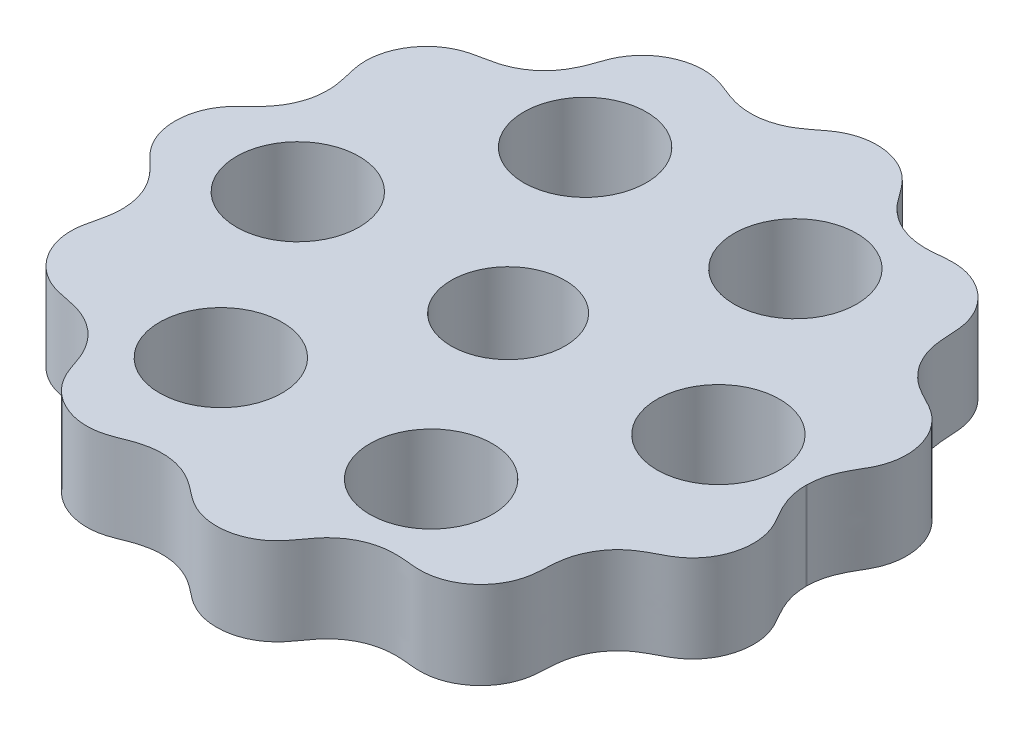
SolidWorks part; units mm, degrees
ref_plane "Front Plane" through (0, 0, 0) normal (0, 0, 1) x (1, 0, 0)
ref_plane "Top Plane" through (0, 0, 0) normal (0, 1, 0) x (1, 0, 0)
ref_plane "Right Plane" through (0, 0, 0) normal (1, 0, 0) x (0, 0, -1)
sketch "Sketch3" plane through (0, 0, 0) normal (0, 1, 0) x (1, 0, 0)
  line L0 (0, 0) -> (12, 0) construction
  circle A2 centre (0, 0) radius 22.0022 construction
  circle A3 centre (0, 0) radius 3.25
  circle A4 centre (12, 0) radius 3.5
  circle A5 centre (6, -10.3923) radius 3.5
  circle A6 centre (-6, -10.3923) radius 3.5
  circle A7 centre (-12, 0) radius 3.5
  circle A8 centre (-6, 10.3923) radius 3.5
  circle A9 centre (6, 10.3923) radius 3.5
  arc A10 (17.0003, 0.0494) -> (17, 0) centre (18.0357, 0.0177) ccw
  spline S0 degree 4 poles (17.0629, 10.5761) (17.1024, 10.5485) (17.1831, 10.4963) (17.3505, 10.4012) (17.7311, 10.208) (18.2739, 9.9208) (18.9393, 9.4712) (19.6343, 8.8352) (20.2276, 8.1035) (20.7083, 7.2937) (21.0679, 6.4232) (21.2996, 5.5105) (21.3985, 4.5738) (21.3612, 3.6327) (21.2084, 2.8227) (20.9929, 2.1509) (20.7619, 1.6146) (20.5771, 1.253) (20.4069, 0.9522) (20.2709, 0.718) (20.1732, 0.544) (20.0996, 0.3974) (20.0548, 0.2883) (20.0293, 0.2059) (20.0151, 0.1485) (20.0054, 0.0954) (19.9994, 0.0221) (19.9995, -0.0231) (20.0056, -0.0976) (20.0157, -0.1515) (20.0305, -0.2103) (20.0576, -0.2961) (20.1054, -0.4102) (20.1837, -0.5637) (20.2872, -0.7462) (20.4299, -0.9919) (20.605, -1.3046) (20.7922, -1.6789) (21.0222, -2.2308) (21.232, -2.918) (21.3741, -3.7456) (21.3939, -4.7048) (21.2722, -5.6618) (21.0101, -6.5953) (20.6114, -7.4854) (20.0808, -8.3094) (19.4318, -9.0448) (18.6765, -9.6692) (17.9593, -10.1033) (17.3838, -10.3747) (17.0159, -10.5949) (16.861, -10.7507) (16.7767, -10.8862) (16.7075, -11.0803) (16.6591, -11.4878) (16.6521, -12.1027) (16.564, -12.9111) (16.3245, -13.8439) (15.9442, -14.7293) (15.4374, -15.5482) (14.8116, -16.287) (14.0807, -16.9293) (13.2585, -17.459) (12.3616, -17.8616) (11.4137, -18.1227) (10.5589, -18.2208) (9.8232, -18.2114) (9.2434, -18.1585) (8.863, -18.1183) (8.5665, -18.1157) (8.3628, -18.1627) (8.2194, -18.2338) (8.0574, -18.3618) (7.797, -18.681) (7.4568, -19.1961) (6.9423, -19.83) (6.2317, -20.4855) (5.4279, -21.024) (4.5537, -21.4367) (3.6266, -21.7155) (2.6684, -21.8557) (1.6984, -21.8537) (0.7392, -21.7074) (-0.1883, -21.4194) (-1.0594, -20.9917) (-1.7352, -20.5281) (-2.2089, -20.1287) (-2.5488, -19.8934) (-2.7398, -19.8138) (-2.897, -19.7836) (-3.1054, -19.7931) (-3.3887, -19.8772) (-3.7411, -20.0221) (-4.2803, -20.2361) (-4.9804, -20.4533) (-5.8246, -20.602) (-6.8039, -20.6219) (-7.7748, -20.4928) (-8.7125, -20.221) (-9.5966, -19.8149) (-10.4092, -19.285) (-11.1316, -18.6426) (-11.751, -17.8996) (-12.248, -17.0704) (-12.563, -16.3174) (-12.7443, -15.7273) (-12.9042, -15.3478) (-13.0235, -15.1793) (-13.1411, -15.0713) (-13.3317, -14.9631) (-13.7448, -14.8538) (-14.3713, -14.7567) (-15.1791, -14.5447) (-16.0776, -14.1626) (-16.9063, -13.6448) (-17.6473, -13.0091) (-18.283, -12.2717) (-18.8012, -11.4523) (-19.1927, -10.5684) (-19.4482, -9.6401) (-19.5636, -8.6834) (-19.5305, -7.721) (-19.3872, -6.9207) (-19.2207, -6.3288) (-19.1523, -5.9241) (-19.1642, -5.7185) (-19.207, -5.5646) (-19.3117, -5.3716) (-19.6027, -5.0567) (-20.0786, -4.6341) (-20.6444, -4.0155) (-21.1932, -3.2033) (-21.6087, -2.3148) (-21.8855, -1.3746) (-22.0173, -0.4082) (-22.0056, 0.5614) (-21.8526, 1.5138) (-21.5633, 2.4285) (-21.1409, 3.29) (-20.6622, 3.9798) (-20.1832, 4.5146) (-19.7733, 4.9083) (-19.5008, 5.1635) (-19.3086, 5.3799) (-19.2098, 5.5586) (-19.1654, 5.7099) (-19.1521, 5.9137) (-19.1968, 6.1997) (-19.2882, 6.5617) (-19.4201, 7.1147) (-19.5338, 7.8237) (-19.5636, 8.663) (-19.453, 9.6163) (-19.2015, 10.5423) (-18.8151, 11.4262) (-18.3005, 12.248) (-17.6671, 12.9896) (-16.9259, 13.6306) (-16.096, 14.1532) (-15.1954, 14.5395) (-14.3851, 14.7539) (-13.7564, 14.8521) (-13.3414, 14.9597) (-13.149, 15.0656) (-13.03, 15.172) (-12.9089, 15.3387) (-12.7477, 15.7162) (-12.5677, 16.3043) (-12.2554, 17.0551) (-11.7627, 17.8827) (-11.1482, 18.6251) (-10.4311, 19.268) (-9.6223, 19.8005) (-8.7401, 20.2108) (-7.8019, 20.4873) (-6.828, 20.6208) (-5.8451, 20.6042) (-4.9974, 20.4574) (-4.2942, 20.2411) (-3.7528, 20.027) (-3.3992, 19.8813) (-3.1154, 19.7953) (-2.9068, 19.7831) (-2.7492, 19.8109) (-2.5577, 19.8882) (-2.2178, 20.1212) (-1.7463, 20.5195) (-1.0739, 20.9828) (-0.2073, 21.4115) (0.7157, 21.7017) (1.6709, 21.8513) (2.639, 21.8576) (3.5979, 21.722) (4.5279, 21.4467) (5.407, 21.036) (6.2156, 20.4983) (6.9308, 19.8426) (7.4486, 19.2074) (7.7905, 18.6908) (8.0504, 18.3693) (8.2113, 18.2391) (8.3536, 18.166) (8.5562, 18.1165) (8.8518, 18.1173) (9.2308, 18.1571) (9.8085, 18.2105) (10.5414, 18.2216) (11.3934, 18.1264) (12.3388, 17.8695) (13.234, 17.472) (14.0571, 16.9469) (14.7909, 16.308) (15.4212, 15.5706) (15.9333, 14.7508) (16.3181, 13.8634) (16.5612, 12.9278) (16.6513, 12.1167) (16.6589, 11.4994) (16.7056, 11.0903) (16.7726, 10.8951) (16.855, 10.7583) (17.0075, 10.6008) (17.3732, 10.3796) (17.9469, 10.1099) (18.6623, 9.6789) (19.4168, 9.059) (20.066, 8.3285) (20.5979, 7.5096) (21, 6.623) (21.2663, 5.6907) (21.3926, 4.7325) (21.3766, 3.7696) (21.2368, 2.9384) (21.0284, 2.248) (20.799, 1.6934) (20.5851, 1.2637) (20.3955, 0.9314) (20.2513, 0.6854) (20.1621, 0.5201) (20.1211, 0.4392) (20.0833, 0.3573) (20.0542, 0.2841) (20.0333, 0.2198) (20.0199, 0.1692) (20.0119, 0.1309) (20.0047, 0.0839) (19.9998, 0.0264) (19.9992, -0.0127) (20.0042, -0.0864) (20.0133, -0.1396) (20.0268, -0.1971) (20.0516, -0.2797) (20.0957, -0.3891) (20.1689, -0.536) (20.2663, -0.71) (20.4023, -0.9443) (20.5727, -1.2448) (20.7579, -1.6062) (20.9896, -2.1421) (21.2061, -2.8134) (21.3601, -3.6231) (21.3988, -4.564) (21.3014, -5.5006) (21.071, -6.4136) (20.7129, -7.2845) (20.2335, -8.095) (19.6414, -8.8276) (18.9476, -9.4646) (18.2831, -9.9152) (17.7408, -10.2031) (17.3601, -10.3961) (17.1925, -10.4908) (17.1115, -10.5425) (17.0719, -10.5698) knots 0 0 0 0 0 0.001143 0.002287 0.004573 0.010154 0.015735 0.021314 0.026894 0.032474 0.038053 0.043633 0.049212 0.054792 0.060372 0.063163 0.065953 0.068667 0.070023 0.07138 0.072395 0.07341 0.073924 0.074181 0.074438 0.074833 0.075229 0.075632 0.076036 0.0763 0.076564 0.077092 0.078165 0.079239 0.080659 0.08208 0.084922 0.087762 0.090603 0.096286 0.101971 0.107653 0.113336 0.119142 0.124948 0.130755 0.13656 0.142365 0.148171 0.15061 0.151699 0.152523 0.153332 0.154393 0.156548 0.162253 0.167957 0.173662 0.179369 0.185074 0.190779 0.196601 0.202423 0.208245 0.214067 0.219889 0.222799 0.22571 0.227909 0.22899 0.229818 0.230629 0.231695 0.233858 0.239585 0.245311 0.251038 0.256767 0.262494 0.268221 0.27397 0.279719 0.285469 0.291218 0.296966 0.302715 0.304886 0.305955 0.30677 0.307594 0.308672 0.310862 0.313762 0.316661 0.322461 0.328262 0.334063 0.339864 0.345664 0.35139 0.357117 0.362845 0.368572 0.374298 0.380024 0.382187 0.383252 0.384064 0.384886 0.385971 0.388401 0.394185 0.399969 0.405752 0.411538 0.417322 0.423106 0.428811 0.434515 0.440221 0.445926 0.451629 0.457334 0.459488 0.460549 0.461358 0.462183 0.463272 0.465711 0.471518 0.477323 0.483129 0.488937 0.494743 0.500549 0.506231 0.511914 0.517598 0.52328 0.528961 0.531802 0.534643 0.53679 0.537846 0.538652 0.539459 0.540515 0.542662 0.545504 0.548346 0.554028 0.559711 0.565396 0.57108 0.576763 0.582568 0.588374 0.59418 0.599985 0.605789 0.611595 0.614033 0.615122 0.615947 0.616756 0.617817 0.619972 0.625677 0.631382 0.637088 0.642795 0.6485 0.654206 0.660027 0.665849 0.67167 0.677492 0.683314 0.686223 0.689133 0.691332 0.692414 0.693241 0.694053 0.695118 0.697281 0.703009 0.708736 0.714464 0.720193 0.725921 0.731648 0.737396 0.743145 0.748894 0.754643 0.76039 0.766138 0.768309 0.769379 0.770193 0.771018 0.772095 0.774286 0.777186 0.780085 0.785886 0.791687 0.797488 0.80329 0.809091 0.814817 0.820543 0.82627 0.831997 0.837722 0.843448 0.84561 0.846676 0.847487 0.848309 0.849394 0.851824 0.857609 0.863393 0.869177 0.874964 0.880748 0.886533 0.892237 0.897941 0.903647 0.909351 0.912202 0.915054 0.917906 0.920757 0.921296 0.921835 0.922373 0.922912 0.923442 0.923707 0.923973 0.924175 0.924377 0.924781 0.925177 0.925573 0.92583 0.926087 0.926601 0.927616 0.928631 0.929987 0.931344 0.934057 0.936847 0.939637 0.945216 0.950795 0.956373 0.961952 0.967531 0.97311 0.978689 0.984268 0.989848 0.995427 0.997714 0.998857 1 1 1 1 1 construction
  spline S1 degree 4 poles (20, 0) (20, -0.0144) (20.0011, -0.0432) (20.0056, -0.0976) (20.0157, -0.1515) (20.0305, -0.2103) (20.0576, -0.2961) (20.1054, -0.4102) (20.1837, -0.5637) (20.2872, -0.7462) (20.4299, -0.9919) (20.605, -1.3046) (20.7922, -1.6789) (21.0222, -2.2308) (21.232, -2.918) (21.3741, -3.7456) (21.3939, -4.7048) (21.2722, -5.6618) (21.0101, -6.5953) (20.6114, -7.4854) (20.0808, -8.3094) (19.4318, -9.0448) (18.6765, -9.6692) (17.9593, -10.1033) (17.3838, -10.3747) (17.0159, -10.5949) (16.861, -10.7507) (16.7767, -10.8862) (16.7075, -11.0803) (16.6591, -11.4878) (16.6521, -12.1027) (16.564, -12.9111) (16.3245, -13.8439) (15.9442, -14.7293) (15.4374, -15.5482) (14.8116, -16.287) (14.0807, -16.9293) (13.2585, -17.459) (12.3616, -17.8616) (11.4137, -18.1227) (10.5589, -18.2208) (9.8232, -18.2114) (9.2434, -18.1585) (8.863, -18.1183) (8.5665, -18.1157) (8.3628, -18.1627) (8.2194, -18.2338) (8.0574, -18.3618) (7.797, -18.681) (7.4568, -19.1961) (6.9423, -19.83) (6.2317, -20.4855) (5.4279, -21.024) (4.5537, -21.4367) (3.6266, -21.7155) (2.6684, -21.8557) (1.6984, -21.8537) (0.7392, -21.7074) (-0.1883, -21.4194) (-1.0594, -20.9917) (-1.7352, -20.5281) (-2.2089, -20.1287) (-2.5488, -19.8934) (-2.7398, -19.8138) (-2.897, -19.7836) (-3.1054, -19.7931) (-3.3887, -19.8772) (-3.7411, -20.0221) (-4.2803, -20.2361) (-4.9804, -20.4533) (-5.8246, -20.602) (-6.8039, -20.6219) (-7.7748, -20.4928) (-8.7125, -20.221) (-9.5966, -19.8149) (-10.4092, -19.285) (-11.1316, -18.6426) (-11.751, -17.8996) (-12.248, -17.0704) (-12.563, -16.3174) (-12.7443, -15.7273) (-12.9042, -15.3478) (-13.0235, -15.1793) (-13.1411, -15.0713) (-13.3317, -14.9631) (-13.7448, -14.8538) (-14.3713, -14.7567) (-15.1791, -14.5447) (-16.0776, -14.1626) (-16.9063, -13.6448) (-17.6473, -13.0091) (-18.283, -12.2717) (-18.8012, -11.4523) (-19.1927, -10.5684) (-19.4482, -9.6401) (-19.5636, -8.6834) (-19.5305, -7.721) (-19.3872, -6.9207) (-19.2207, -6.3288) (-19.1523, -5.9241) (-19.1642, -5.7185) (-19.207, -5.5646) (-19.3117, -5.3716) (-19.6027, -5.0567) (-20.0786, -4.6341) (-20.6444, -4.0155) (-21.1932, -3.2033) (-21.6087, -2.3148) (-21.8855, -1.3746) (-22.0173, -0.4082) (-22.0056, 0.5614) (-21.8526, 1.5138) (-21.5633, 2.4285) (-21.1409, 3.29) (-20.6622, 3.9798) (-20.1832, 4.5146) (-19.7733, 4.9083) (-19.5008, 5.1635) (-19.3086, 5.3799) (-19.2098, 5.5586) (-19.1654, 5.7099) (-19.1521, 5.9137) (-19.1968, 6.1997) (-19.2882, 6.5617) (-19.4201, 7.1147) (-19.5338, 7.8237) (-19.5636, 8.663) (-19.453, 9.6163) (-19.2015, 10.5423) (-18.8151, 11.4262) (-18.3005, 12.248) (-17.6671, 12.9896) (-16.9259, 13.6306) (-16.096, 14.1532) (-15.1954, 14.5395) (-14.3851, 14.7539) (-13.7564, 14.8521) (-13.3414, 14.9597) (-13.149, 15.0656) (-13.03, 15.172) (-12.9089, 15.3387) (-12.7477, 15.7162) (-12.5677, 16.3043) (-12.2554, 17.0551) (-11.7627, 17.8827) (-11.1482, 18.6251) (-10.4311, 19.268) (-9.6223, 19.8005) (-8.7401, 20.2108) (-7.8019, 20.4873) (-6.828, 20.6208) (-5.8451, 20.6042) (-4.9974, 20.4574) (-4.2942, 20.2411) (-3.7528, 20.027) (-3.3992, 19.8813) (-3.1154, 19.7953) (-2.9068, 19.7831) (-2.7492, 19.8109) (-2.5577, 19.8882) (-2.2178, 20.1212) (-1.7463, 20.5195) (-1.0739, 20.9828) (-0.2073, 21.4115) (0.7157, 21.7017) (1.6709, 21.8513) (2.639, 21.8576) (3.5979, 21.722) (4.5279, 21.4467) (5.407, 21.036) (6.2156, 20.4983) (6.9308, 19.8426) (7.4486, 19.2074) (7.7905, 18.6908) (8.0504, 18.3693) (8.2113, 18.2391) (8.3536, 18.166) (8.5562, 18.1165) (8.8518, 18.1173) (9.2308, 18.1571) (9.8085, 18.2105) (10.5414, 18.2216) (11.3934, 18.1264) (12.3388, 17.8695) (13.234, 17.472) (14.0571, 16.9469) (14.7909, 16.308) (15.4212, 15.5706) (15.9333, 14.7508) (16.3181, 13.8634) (16.5612, 12.9278) (16.6513, 12.1167) (16.6589, 11.4994) (16.7056, 11.0903) (16.7726, 10.8951) (16.855, 10.7583) (17.0075, 10.6008) (17.3732, 10.3796) (17.9469, 10.1099) (18.6623, 9.6789) (19.4168, 9.059) (20.066, 8.3285) (20.5979, 7.5096) (21, 6.623) (21.2663, 5.6907) (21.3926, 4.7325) (21.3766, 3.7696) (21.2368, 2.9384) (21.0284, 2.248) (20.799, 1.6934) (20.5851, 1.2637) (20.3955, 0.9314) (20.2513, 0.6854) (20.1621, 0.5201) (20.1211, 0.4392) (20.0833, 0.3573) (20.0542, 0.2841) (20.0333, 0.2198) (20.0199, 0.1692) (20.0119, 0.1309) (20.0047, 0.0839) (20.0014, 0.0453) (20.0003, 0.0236) (20.0001, 0.0091) knots 0.075229 0.075229 0.075229 0.075229 0.075229 0.075632 0.076036 0.0763 0.076564 0.077092 0.078165 0.079239 0.080659 0.08208 0.084922 0.087762 0.090603 0.096286 0.101971 0.107653 0.113336 0.119142 0.124948 0.130755 0.13656 0.142365 0.148171 0.15061 0.151699 0.152523 0.153332 0.154393 0.156548 0.162253 0.167957 0.173662 0.179369 0.185074 0.190779 0.196601 0.202423 0.208245 0.214067 0.219889 0.222799 0.22571 0.227909 0.22899 0.229818 0.230629 0.231695 0.233858 0.239585 0.245311 0.251038 0.256767 0.262494 0.268221 0.27397 0.279719 0.285469 0.291218 0.296966 0.302715 0.304886 0.305955 0.30677 0.307594 0.308672 0.310862 0.313762 0.316661 0.322461 0.328262 0.334063 0.339864 0.345664 0.35139 0.357117 0.362845 0.368572 0.374298 0.380024 0.382187 0.383252 0.384064 0.384886 0.385971 0.388401 0.394185 0.399969 0.405752 0.411538 0.417322 0.423106 0.428811 0.434515 0.440221 0.445926 0.451629 0.457334 0.459488 0.460549 0.461358 0.462183 0.463272 0.465711 0.471518 0.477323 0.483129 0.488937 0.494743 0.500549 0.506231 0.511914 0.517598 0.52328 0.528961 0.531802 0.534643 0.53679 0.537846 0.538652 0.539459 0.540515 0.542662 0.545504 0.548346 0.554028 0.559711 0.565396 0.57108 0.576763 0.582568 0.588374 0.59418 0.599985 0.605789 0.611595 0.614033 0.615122 0.615947 0.616756 0.617817 0.619972 0.625677 0.631382 0.637088 0.642795 0.6485 0.654206 0.660027 0.665849 0.67167 0.677492 0.683314 0.686223 0.689133 0.691332 0.692414 0.693241 0.694053 0.695118 0.697281 0.703009 0.708736 0.714464 0.720193 0.725921 0.731648 0.737396 0.743145 0.748894 0.754643 0.76039 0.766138 0.768309 0.769379 0.770193 0.771018 0.772095 0.774286 0.777186 0.780085 0.785886 0.791687 0.797488 0.80329 0.809091 0.814817 0.820543 0.82627 0.831997 0.837722 0.843448 0.84561 0.846676 0.847487 0.848309 0.849394 0.851824 0.857609 0.863393 0.869177 0.874964 0.880748 0.886533 0.892237 0.897941 0.903647 0.909351 0.912202 0.915054 0.917906 0.920757 0.921296 0.921835 0.922373 0.922912 0.923442 0.923707 0.923973 0.924175 0.924377 0.924781 0.924781 0.924781 0.924781 0.924781 construction
  spline S2 degree 1 poles (17, 0) (17.0003, 0.0494) knots 0 0 1 1 construction
  spline S3 degree 3 poles (17, 0) (17, -0.064) (17.0046, -0.2046) (17.0152, -0.3391) (17.0345, -0.5175) (17.0827, -0.7982) (17.1416, -1.0262) (17.2492, -1.3628) (17.3851, -1.6775) (17.5575, -2.0175) (17.7097, -2.2809) (17.8345, -2.4977) (17.9317, -2.6736) (18.0371, -2.8792) (18.1419, -3.1163) (18.2386, -3.3968) (18.31, -3.6825) (18.3561, -3.974) (18.3837, -4.3697) (18.3535, -4.8716) (18.2141, -5.4633) (17.977, -6.0217) (17.7049, -6.4423) (17.4493, -6.7434) (17.2418, -6.9481) (17.0133, -7.1374) (16.755, -7.3161) (16.5288, -7.4481) (16.2604, -7.5885) (15.9871, -7.7304) (15.6208, -7.9275) (14.9611, -8.359) (14.3181, -9.1135) (13.8537, -10.011) (13.7028, -10.8621) (13.6757, -11.2934) (13.6584, -11.6155) (13.6467, -11.8477) (13.6281, -12.0842) (13.5931, -12.3439) (13.5277, -12.6429) (13.4407, -12.9216) (13.292, -13.2833) (13.0427, -13.7179) (12.6563, -14.1822) (12.1935, -14.5775) (11.6727, -14.8863) (11.2084, -15.0627) (10.8255, -15.153) (10.534, -15.1954) (10.2341, -15.2126) (9.9623, -15.2064) (9.703, -15.1874) (9.4592, -15.1638) (9.1125, -15.133) (8.6065, -15.1039) (7.8968, -15.178) (7.1871, -15.3794) (6.5156, -15.7451) (5.8842, -16.2697) (5.5148, -16.7368) (5.3092, -17.0172) (5.1442, -17.2495) (4.9849, -17.4663) (4.8201, -17.6683) (4.6048, -17.8936) (4.3837, -18.0878) (4.1486, -18.2605) (3.8094, -18.4664) (3.1689, -18.7496) (2.3551, -18.8796) (1.6573, -18.8107) (1.2693, -18.7208) (0.9903, -18.6298) (0.7215, -18.5152) (0.4534, -18.3721) (0.2338, -18.2306) (0.0468, -18.0944) (-0.127, -17.9598) (-0.3665, -17.7725) (-0.674, -17.5369) (-1.2968, -17.1327) (-2.1802, -16.8412) (-2.9707, -16.7655) (-3.5926, -16.8331) (-4.1828, -16.9752) (-4.572, -17.1233) (-4.872, -17.242) (-5.1492, -17.3523) (-5.4209, -17.4467) (-5.7191, -17.5258) (-6.009, -17.5767) (-6.4011, -17.6107) (-6.8954, -17.5883) (-7.6826, -17.4142) (-8.413, -17.0391) (-8.934, -16.5704) (-9.1906, -16.2712) (-9.3598, -16.0342) (-9.5118, -15.7768) (-9.6257, -15.5403) (-9.7081, -15.3396) (-9.7741, -15.1624) (-9.8578, -14.9196) (-9.9694, -14.6096) (-10.1275, -14.1829) (-10.4661, -13.5787) (-10.892, -13.0387) (-11.4956, -12.5406) (-12.2676, -12.1389) (-12.889, -11.9785) (-13.2431, -11.9047) (-13.53, -11.8496) (-13.7354, -11.8074) (-13.9547, -11.7555) (-14.2053, -11.6804) (-14.4872, -11.5699) (-14.7486, -11.4402) (-15.083, -11.2358) (-15.4732, -10.9209) (-15.8712, -10.4662) (-16.1892, -9.9459) (-16.4113, -9.3862) (-16.5129, -8.8962) (-16.5413, -8.5085) (-16.5373, -8.2138) (-16.5057, -7.9018) (-16.4594, -7.6446) (-16.3961, -7.3716) (-16.3252, -7.0796) (-16.2437, -6.7189) (-16.1308, -6.0486) (-16.1984, -5.1514) (-16.4216, -4.4025) (-16.7419, -3.8142) (-17.1392, -3.2881) (-17.4493, -2.9811) (-17.6791, -2.7573) (-17.8618, -2.5831) (-18.0379, -2.4065) (-18.2105, -2.2138) (-18.3971, -1.9683) (-18.5536, -1.7201) (-18.6873, -1.4603) (-18.8375, -1.0922) (-18.9651, -0.6082) (-19.0172, -0.0022) (-18.966, 0.6026) (-18.8388, 1.0883) (-18.69, 1.4544) (-18.5555, 1.7168) (-18.3984, 1.9665) (-18.218, 2.2047) (-18.039, 2.4049) (-17.8605, 2.5848) (-17.6944, 2.7435) (-17.4589, 2.9703) (-17.1487, 3.279) (-16.7647, 3.7814) (-16.4432, 4.3523) (-16.2061, 5.105) (-16.1286, 6.0195) (-16.2371, 6.6891) (-16.3263, 7.0853) (-16.3942, 7.3605) (-16.456, 7.6297) (-16.5061, 7.9049) (-16.537, 8.2072) (-16.5415, 8.5018) (-16.5133, 8.894) (-16.4131, 9.3796) (-16.1911, 9.9422) (-15.8743, 10.4619) (-15.4767, 10.9176) (-15.087, 11.2329) (-14.7529, 11.4379) (-14.4915, 11.568) (-14.21, 11.6788) (-13.9601, 11.754) (-13.7412, 11.8061) (-13.5368, 11.8482) (-13.254, 11.9027) (-12.9047, 11.9751) (-12.2982, 12.1292) (-11.5368, 12.5144) (-10.9277, 13.0022) (-10.4882, 13.5449) (-10.1362, 14.1617) (-9.9745, 14.5959) (-9.8606, 14.911) (-9.7763, 15.1563) (-9.7103, 15.3341) (-9.628, 15.5353) (-9.514, 15.7726) (-9.3624, 16.0302) (-9.1936, 16.2673) (-8.9374, 16.567) (-8.4173, 17.0363) (-7.6873, 17.4124) (-6.9002, 17.5877) (-6.4059, 17.6107) (-6.0138, 17.5773) (-5.7239, 17.5269) (-5.4258, 17.4482) (-5.1551, 17.3545) (-4.8796, 17.2451) (-4.5838, 17.128) (-4.2022, 16.982) (-3.6268, 16.8397) (-3.0183, 16.7668) (-2.2309, 16.8306) (-1.3303, 17.1146) (-0.6879, 17.5264) (-0.3761, 17.765) (-0.1328, 17.9552) (0.0419, 18.0908) (0.2291, 18.2274) (0.4492, 18.3695) (0.7173, 18.5131) (0.9858, 18.6281) (1.2646, 18.7195) (1.6525, 18.8099) (2.35, 18.8798) (3.164, 18.751) (3.8051, 18.4686) (4.1446, 18.2633) (4.38, 18.0908) (4.6014, 17.8969) (4.8166, 17.6723) (4.9814, 17.4708) (5.1402, 17.255) (5.3032, 17.0257) (5.5055, 16.7491) (5.8649, 16.2918) (6.4774, 15.7721) (7.1392, 15.3991) (7.8546, 15.1856) (8.5813, 15.1034) (9.0977, 15.1319) (9.4503, 15.1629) (9.6959, 15.1868) (9.9567, 15.2061) (10.2291, 15.2127) (10.5292, 15.1959) (10.8208, 15.1539) (11.2037, 15.0641) (11.6683, 14.8884) (12.1894, 14.5804) (12.6528, 14.1857) (13.0399, 13.7219) (13.2898, 13.2877) (13.4391, 12.9262) (13.5265, 12.6474) (13.5922, 12.3489) (13.6275, 12.0899) (13.6463, 11.8539) (13.6581, 11.6233) (13.6748, 11.3065) (13.7016, 10.8812) (13.8419, 10.0529) (14.2893, 9.157) (14.9287, 8.3851) (15.6048, 7.9361) (15.9758, 7.7364) (16.2536, 7.5919) (16.5238, 7.4509) (16.7504, 7.3191) (17.0095, 7.1403) (17.2382, 6.9513) (17.4459, 6.7471) (17.702, 6.4462) (17.9746, 6.0261) (18.2125, 5.4681) (18.3528, 4.8765) (18.3836, 4.3746) (18.3566, 3.9788) (18.3109, 3.6872) (18.24, 3.4015) (18.1436, 3.1207) (18.0396, 2.8844) (17.9343, 2.6784) (17.8385, 2.5044) (17.7138, 2.2886) (17.5651, 2.0293) (17.3945, 1.7001) (17.2332, 1.3181) (17.0977, 0.9158) (17.0229, 0.4303) (17.0078, 0.2524) (17.0012, 0.1129) (17.0003, 0.0494) knots 0.075229 0.075229 0.075229 0.075229 0.075437 0.075644 0.075851 0.076059 0.076474 0.076888 0.077718 0.078548 0.080207 0.081866 0.083526 0.085185 0.088503 0.091822 0.095141 0.098459 0.101778 0.108415 0.115052 0.121689 0.128326 0.131645 0.134963 0.138282 0.1416 0.144919 0.146578 0.148238 0.149897 0.151556 0.152386 0.153215 0.154875 0.156534 0.158193 0.159853 0.161512 0.16483 0.168149 0.171468 0.174786 0.181423 0.18806 0.194697 0.201335 0.207972 0.21129 0.214609 0.217927 0.221246 0.222905 0.224565 0.226224 0.227883 0.228713 0.229542 0.230372 0.231202 0.232861 0.23452 0.236179 0.237839 0.241157 0.244476 0.247794 0.251113 0.254432 0.261069 0.274343 0.28098 0.284299 0.287617 0.290936 0.294254 0.297573 0.299232 0.300891 0.302551 0.30421 0.305869 0.306699 0.307529 0.308358 0.309188 0.310847 0.312506 0.314166 0.317484 0.320803 0.324121 0.32744 0.334077 0.340714 0.353989 0.360626 0.363944 0.367263 0.370581 0.3739 0.375559 0.377218 0.378878 0.380537 0.382196 0.383026 0.383856 0.384685 0.385515 0.387174 0.388833 0.390493 0.392152 0.393811 0.39713 0.400448 0.403767 0.407086 0.413723 0.42036 0.426997 0.433634 0.440271 0.44359 0.446908 0.450227 0.453545 0.455205 0.456864 0.458523 0.460183 0.461012 0.461842 0.462671 0.463501 0.46516 0.46682 0.468479 0.470138 0.473457 0.476775 0.480094 0.483412 0.486731 0.493368 0.500005 0.506642 0.51328 0.516598 0.519917 0.523235 0.526554 0.529872 0.531532 0.533191 0.53485 0.536509 0.537339 0.538169 0.538998 0.539828 0.541487 0.543147 0.544806 0.546465 0.549784 0.553102 0.556421 0.559739 0.566377 0.573014 0.579651 0.586288 0.592925 0.596244 0.599562 0.602881 0.606199 0.607859 0.609518 0.611177 0.612836 0.614496 0.615325 0.616155 0.616985 0.617814 0.619474 0.621133 0.622792 0.624451 0.626111 0.629429 0.632748 0.636066 0.639385 0.646022 0.659296 0.665933 0.672571 0.675889 0.679208 0.682526 0.685845 0.687504 0.689163 0.690823 0.691652 0.692482 0.693312 0.694141 0.695801 0.69746 0.699119 0.700778 0.702438 0.705756 0.709075 0.712393 0.715712 0.71903 0.725668 0.738942 0.745579 0.748898 0.752216 0.755535 0.758853 0.762172 0.763831 0.76549 0.76715 0.768809 0.769639 0.770468 0.771298 0.772128 0.773787 0.775446 0.777105 0.778765 0.782083 0.785402 0.78872 0.792039 0.798676 0.805313 0.81195 0.818587 0.825225 0.828543 0.831862 0.83518 0.838499 0.840158 0.841817 0.843477 0.845136 0.846795 0.847625 0.848454 0.850114 0.851773 0.853432 0.855092 0.85841 0.861729 0.865047 0.868366 0.871684 0.878322 0.884959 0.891596 0.898233 0.901551 0.90487 0.908189 0.911507 0.914826 0.916485 0.918144 0.919804 0.921463 0.922293 0.923122 0.923952 0.924367 0.924574 0.924781 0.924781 0.924781 0.924781
  point P27 (0, 0)
  dimension "D2" = 6.5
  dimension "D3" = 7
  dimension "D1" = 3
  dimension "D4" = 6
extrude "Boss-Extrude1" add sketch "Sketch3" along normal blind 5
